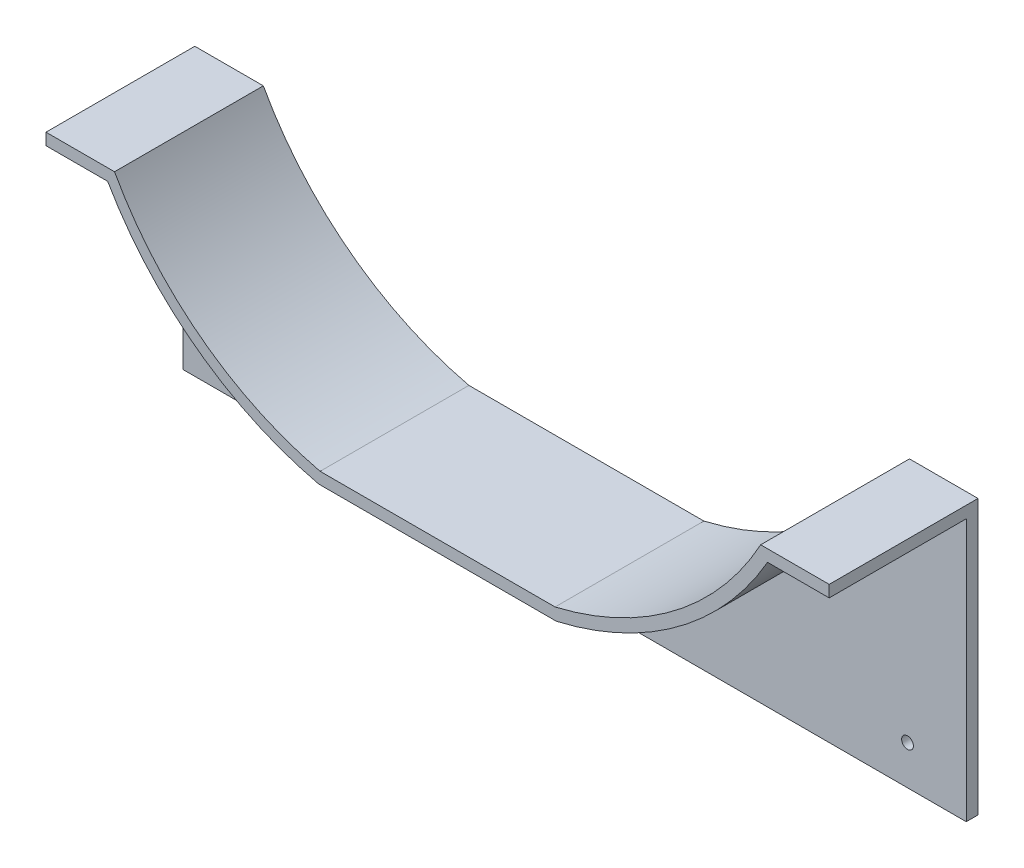
SolidWorks part; units mm, degrees
ref_plane "前视基准面" through (0, 0, 0) normal (0, 0, 1) x (1, 0, 0)
ref_plane "上视基准面" through (0, 0, 0) normal (0, 1, 0) x (1, 0, 0)
ref_plane "右视基准面" through (0, 0, 0) normal (1, 0, 0) x (0, 0, -1)
sketch "草图1" plane through (0, 0, 0) normal (0, 0, 1) x (1, 0, 0)
  line L0 (100, -30) -> (100, 68.9094) construction
  line L1 (0, 0) -> (200, 0)
  line L2 (0, 0) -> (0, -30)
  line L3 (0, -30) -> (200, -30)
  line L4 (200, 0) -> (200, -30)
  line L5 (200, 0) -> (130, 0)
  line L6 (200, 0) -> (200, 40)
  line L7 (200, 40) -> (182.5, 40)
  line L9 (100, 33.2047) -> (130, 33.2047) construction
  line L11 (0, 40) -> (17.5, 40)
  line L12 (0, 0) -> (0, 40)
  line L13 (0, 0) -> (70, 0)
  arc A0 (17.5, 40) -> (70, 0) centre (88.6536, 78.936) ccw
  arc A1 (182.5, 40) -> (130, 0) centre (111.3464, 78.936) cw
  dimension "D1" = 200
  dimension "D2" = 30
  dimension "D3" = 30
  dimension "D4" = 40
extrude "凸台-拉伸1" add sketch "草图1" along normal blind 3
sketch "草图2" plane through (0, 0, 3) normal (0, 0, 1) x (1, 0, 0)
  line L0 (200, 40) -> (200, -30) construction
  line L1 (0, -30) -> (200, -30) construction
  line L2 (0, -30) -> (0, -10) construction
  line L3 (0, -10) -> (200, -10) construction
  line L4 (200, -30) -> (200, -10) construction
  line L5 (200, -20) -> (0, -20) construction
  line L6 (200, -20) -> (185, -20) construction
  line L7 (100, -30) -> (100, -10) construction
  circle A0 centre (185, -20) radius 1.5
  circle A1 centre (100, -20) radius 1.5
  circle A2 centre (15, -20) radius 1.5
  dimension "D2" = 3
  dimension "D3" = 3
  dimension "D1" = 20
  dimension "D4" = 15
extrude "切除-拉伸1" cut sketch "草图2" against normal up to surface (3 mm away) up to face at (100, 11.1046, 0)
sketch "草图14" plane through (0, 40, 0) normal (0, 1, 0) x (1, 0, 0)
  line L1 (200, 0) -> (0, 0)
  line L2 (200, 0) -> (200, -10.4582)
  line L3 (200, -10.4582) -> (0, -10.4582)
  line L4 (0, 0) -> (0, -10.4582)
sketch "草图15" plane through (0, 0, 3) normal (0, 0, 1) x (1, 0, 0)
  line L4 (130.3464, -3) -> (69.6536, -3)
  line L6 (200, -30) -> (200, 40)
  line L7 (200, 40) -> (182.5, 40)
  line L8 (130, 0) -> (70, 0)
  line L9 (17.5, 40) -> (0, 40)
  line L10 (0, 40) -> (0, -30)
  line L11 (0, -30) -> (200, -30)
  line L13 (200, 40) -> (182.5, 40)
  line L14 (130, 0) -> (70, 0)
  line L18 (17.5, 40) -> (0, 40) construction
  line L19 (15.7435, 37) -> (3, 37) construction
  line L20 (3, 37) -> (3, -27) construction
  line L21 (0, 40) -> (0, -30) construction
  line L22 (3, -27) -> (197, -27) construction
  line L23 (0, -30) -> (200, -30) construction
  line L24 (197, -27) -> (197, 37) construction
  line L25 (200, -30) -> (200, 40) construction
  line L26 (197, 37) -> (184.2565, 37) construction
  line L27 (15.7435, 37) -> (0, 37)
  line L28 (0, 40) -> (0, -30) construction
  line L29 (184.2565, 37) -> (200, 37)
  line L30 (200, 40) -> (200, -30) construction
  line L31 (200, 37) -> (200, 40)
  line L32 (0, 37) -> (0, 40)
  line L33 (0, 40) -> (17.5, 40)
  line L34 (182.5, 40) -> (200, 40)
  arc A0 (130.3464, -3) -> (184.2565, 37) centre (111.3464, 78.936) ccw
  arc A1 (15.7435, 37) -> (69.6536, -3) centre (88.6536, 78.936) ccw
  arc A2 (130, 0) -> (182.5, 40) centre (111.3464, 78.936) ccw
  arc A3 (17.5, 40) -> (70, 0) centre (88.6536, 78.936) ccw
  arc A4 (130, 0) -> (182.5, 40) centre (111.3464, 78.936) ccw
  arc A5 (17.5, 40) -> (70, 0) centre (88.6536, 78.936) ccw
  line M28 (200, -30) -> (200, 40)
  line M29 (200, 40) -> (182.5, 40)
  arc M30 (182.5, 40) -> (130, 0) centre (111.3464, 78.936) cw
  line M31 (130, 0) -> (70, 0)
  arc M32 (70, 0) -> (17.5, 40) centre (88.6536, 78.936) cw
  line M33 (17.5, 40) -> (0, 40)
  line M34 (0, 40) -> (0, -30)
  dimension "D1" = 0
  dimension "D2" = 3
extrude "凸台-拉伸2" add sketch "草图15" along normal blind 35 contours L27 A1 L4 A0 L29 M28 M29 M30 M31 M32 M33 M34
